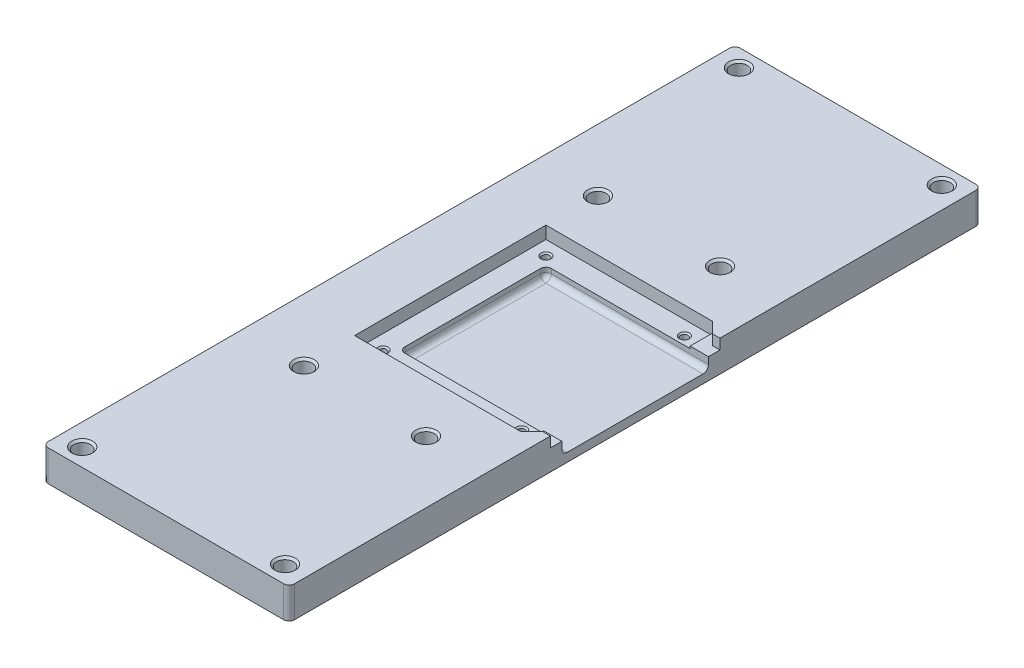
SolidWorks part; units mm, degrees
ref_plane "Front Plane" through (0, 0, 0) normal (0, 0, 1) x (1, 0, 0)
ref_plane "Top Plane" through (0, 0, 0) normal (0, 1, 0) x (1, 0, 0)
ref_plane "Right Plane" through (0, 0, 0) normal (1, 0, 0) x (0, 0, -1)
sketch "Sketch1" plane through (0, 0, 0) normal (0, 1, 0) x (1, 0, 0)
  line L0 (0, -112.5) -> (0, 112.5) construction
  line L1 (45.375, 112.5) -> (-45.375, 112.5) construction
  line L2 (-45.375, 112.5) -> (-45.375, -112.5)
  line L3 (-45.375, 0) -> (45.375, 0) construction
  line L4 (-45.375, 112.5) -> (-45.375, 125.5)
  line L5 (-43.375, 127.5) -> (43.375, 127.5)
  line L6 (0, 127.5) -> (0, 112.5) construction
  line L7 (45.375, 112.5) -> (45.375, 125.5)
  line L8 (45.375, 112.5) -> (45.375, -112.5)
  line L9 (0, -127.5) -> (0, -112.5) construction
  line L10 (45.375, -112.5) -> (-45.375, -112.5) construction
  line L11 (45.375, -112.5) -> (45.375, -125.5)
  line L12 (-43.375, -127.5) -> (43.375, -127.5)
  line L13 (-45.375, -112.5) -> (-45.375, -125.5)
  line L14 (-45.375, 115.5) -> (45.375, 115.5) construction
  circle A1 centre (-37.375, 121) radius 3.075 construction
  circle A2 centre (37.375, 121) radius 3.075 construction
  circle A5 centre (37.375, -121) radius 3.075 construction
  circle A6 centre (-37.375, -121) radius 3.075 construction
  arc A8 (-43.375, -127.5) -> (-45.375, -125.5) centre (-43.375, -125.5) cw
  arc A9 (45.375, -125.5) -> (43.375, -127.5) centre (43.375, -125.5) cw
  arc A10 (45.375, 125.5) -> (43.375, 127.5) centre (43.375, 125.5) ccw
  arc A11 (-45.375, 125.5) -> (-43.375, 127.5) centre (-43.375, 125.5) cw
  circle A12 centre (-22.5, 54.175) radius 3.075 construction
  circle A13 centre (22.5, 54.175) radius 3.075 construction
  circle A14 centre (22.5, -54.175) radius 3.075 construction
  circle A15 centre (-22.5, -54.175) radius 3.075 construction
  point P24 (0, 0)
  point P36 (-45.375, -127.5)
  point P39 (45.375, -127.5)
  point P42 (45.375, 127.5)
  point P45 (-45.375, 127.5)
  dimension "D5" = 22.5
  dimension "D10" = 2
  dimension "D3" = 6.15
  dimension "D1" = 45.375
  dimension "D2" = 112.5
  dimension "D4" = 6.5
  dimension "D6" = 8
  dimension "D7" = 8.5
  dimension "D8" = 12
  dimension "D9" = 3
  dimension "D11" = 127.5
  dimension "D12" = 54.175
extrude "Boss-Extrude1" add sketch "Sketch1" along normal blind 11.5
sketch "Sketch3" plane through (0, 11.5, 0) normal (0, 1, 0) x (1, 0, 0)
  line L0 (0, 0) -> (-45.375, 0) construction
  line L1 (-45.375, 125.5) -> (-45.375, -125.5) construction
  line L2 (0, 0) -> (0, 127.5) construction
  line L3 (43.375, 127.5) -> (-43.375, 127.5) construction
  line L4 (3.96, -16.3) -> (3.96, 16.3)
  line L5 (-2.46, -17.8) -> (2.46, -17.8)
  line L6 (-3.96, 16.3) -> (-3.96, -16.3)
  line L7 (2.46, 17.8) -> (-2.46, 17.8)
  line L8 (0, 17.8) -> (0, -17.8) construction
  line L9 (13.25, 0) -> (0, 0) construction
  line L10 (16.15, 10.025) -> (10.35, 10.025)
  line L11 (16.15, 10.025) -> (16.15, -10.025)
  line L12 (16.15, -10.025) -> (10.35, -10.025)
  line L13 (10.35, 10.025) -> (10.35, -10.025)
  line L14 (16.15, 10.025) -> (10.35, -10.025) construction
  line L15 (16.15, -10.025) -> (10.35, 10.025) construction
  line L16 (13.25, 0) -> (13.25, 10.025) construction
  line L17 (-16.15, 10.025) -> (-16.15, -10.025)
  line L18 (-16.15, -10.025) -> (-10.35, -10.025)
  line L23 (-16.15, 10.025) -> (-10.35, 10.025)
  line L24 (-10.35, 10.025) -> (-10.35, -10.025)
  arc A0 (-2.46, 17.8) -> (-3.96, 16.3) centre (-2.46, 16.3) ccw
  arc A1 (3.96, 16.3) -> (2.46, 17.8) centre (2.46, 16.3) ccw
  arc A2 (2.46, -17.8) -> (3.96, -16.3) centre (2.46, -16.3) ccw
  arc A3 (-3.96, -16.3) -> (-2.46, -17.8) centre (-2.46, -16.3) ccw
  point P9 (0, 0)
  point P23 (0, 0)
  dimension "D2" = 1.5
  dimension "D1" = 35.6
  dimension "D3" = 7.92
  dimension "D4" = 20.05
  dimension "D5" = 5.8
  dimension "D6" = 13.25
sketch "Sketch4" plane through (0, 11.5, 0) normal (0, 1, 0) x (1, 0, 0)
  circle A0 centre (-37.375, -121) radius 3.075 construction
  circle A1 centre (37.375, -121) radius 3.075 construction
  circle A2 centre (37.375, 121) radius 3.075 construction
  circle A3 centre (-22.5, -54.175) radius 3.075 construction
  circle A4 centre (22.5, -54.175) radius 3.075 construction
  circle A5 centre (-37.375, 121) radius 3.075 construction
  circle A6 centre (22.5, 54.175) radius 3.075 construction
  circle A7 centre (-22.5, 54.175) radius 3.075 construction
  circle A8 centre (-37.375, -121) radius 3.075
  circle A9 centre (37.375, -121) radius 3.075
  circle A10 centre (37.375, 121) radius 3.075
  circle A13 centre (-37.375, 121) radius 3.075
  circle A14 centre (-22.5, -54.175) radius 3.075
  circle A15 centre (22.5, -54.175) radius 3.075
  circle A16 centre (22.5, 54.175) radius 3.075
  circle A17 centre (-22.5, 54.175) radius 3.075
extrude "Cut-Extrude1" cut sketch "Sketch4" against normal blind 6
sketch "Sketch21" plane through (0, 11.5, 0) normal (0, 1, 0) x (1, 0, 0)
  line L0 (38.5, 35) -> (-22.5, 35) construction
  line L1 (38.5, 35) -> (42.5, 31) construction
  line L2 (-22.5, 35) -> (-22.5, -35) construction
  line L3 (-22.5, 0) -> (0, 0) construction
  line L4 (0, 0) -> (38.5, 0) construction
  line L5 (38.5, -35) -> (38.5, 35) construction
  line L6 (38.5, -35) -> (-22.5, -35) construction
  line L7 (42.5, 31) -> (45.375, 31) construction
  line L8 (45.375, -125.5) -> (45.375, 125.5) construction
  line L9 (45.375, 31) -> (45.375, -31)
  line L10 (45.375, 0) -> (38.5, 0) construction
  line L11 (42.5, -31) -> (45.375, -31) construction
  line L12 (38.5, -35) -> (42.5, -31) construction
  line L13 (42.6036, 31.25) -> (45.375, 31.25)
  line L14 (38.6036, 35.25) -> (42.6036, 31.25)
  line L15 (38.6036, 35.25) -> (-22.75, 35.25)
  line L16 (-22.75, 35.25) -> (-22.75, -35.25)
  line L17 (38.6036, -35.25) -> (-22.75, -35.25)
  line L18 (38.6036, -35.25) -> (42.6036, -31.25)
  line L19 (42.6036, -31.25) -> (45.375, -31.25)
  line L20 (45.375, -31.25) -> (45.375, -31)
  line L21 (45.375, 31) -> (45.375, 31.25)
  circle A0 centre (-17.5, 30) radius 1.6 construction
  circle A1 centre (33.5, 30) radius 1.6 construction
  circle A2 centre (33.5, -30) radius 1.6 construction
  circle A3 centre (-17.5, -30) radius 1.6 construction
  dimension "D8" = 3.2
  dimension "D1" = 22.5
  dimension "D2" = 61
  dimension "D3" = 35
  dimension "D4" = 5
  dimension "D5" = 5
  dimension "D6" = 5
  dimension "D7" = 5
  dimension "D9" = 45
  dimension "D10" = 4
  dimension "D12" = 2.875
  dimension "D11" = 0.25
extrude "Cut-Extrude6" cut sketch "Sketch21" against normal blind 4.6
sketch "Sketch24" plane through (0, 6.9, 0) normal (0, 1, 0) x (1, 0, 0)
  line L0 (45.375, 27) -> (-14.5, 27)
  line L2 (-14.5, 27) -> (-14.5, -27)
  line L3 (-14.5, -27) -> (45.375, -27)
  line L4 (45.375, -27) -> (45.375, 27)
  line L8 (38.5, 35) -> (-22.5, 35) construction
  line L10 (-22.5, 35) -> (-22.5, -35) construction
  line L11 (38.5, -35) -> (-22.5, -35) construction
  line L12 (45.375, -31.25) -> (45.375, 31.25) construction
  dimension "D1" = 8
  dimension "D2" = 8
  dimension "D3" = 8
extrude "Cut-Extrude3" cut sketch "Sketch24" against normal blind 3.7 and the other way through all
sketch "Sketch25" plane through (0, 6.9, 0) normal (0, 1, 0) x (1, 0, 0)
  circle A0 centre (33.5, 30) radius 1.35
  circle A1 centre (-17.5, 30) radius 1.35
  circle A2 centre (33.5, -30) radius 1.35
  circle A3 centre (-17.5, -30) radius 1.35
  dimension "D1" = 2.7
extrude "Cut-Extrude4" cut sketch "Sketch25" against normal blind 5
chamfer "Chamfer4" distance 0.5 angle 45 4 edges at (-17.5, 6.9, 31.35) (33.5, 6.9, 31.35) (33.5, 6.9, -28.65) (-17.5, 6.9, -28.65)
fillet "Fillet1" radius 2 5 edges at (15.4375, 3.2, 27) (-14.5, 5.05, 27) (-14.5, 5.05, -27) (-14.5, 3.2, 0) (15.4375, 3.2, -27)
sketch "Sketch26" plane through (0, 6.9, 0) normal (0, 1, 0) x (1, 0, 0)
  line L0 (0, 0) -> (45.375, 0) construction
  line L1 (45.375, -25) -> (45.375, 25) construction
  line L2 (38.6036, 35.25) -> (38.6036, 27)
  line L3 (45.375, 27) -> (-12.5, 27) construction
  line L4 (38.6036, 27) -> (45.375, 27)
  line L5 (45.375, 27) -> (45.375, 31.25)
  line L6 (45.375, 31.25) -> (42.6036, 31.25)
  line L7 (42.6036, 31.25) -> (38.6036, 35.25)
  line L8 (42.6036, -31.25) -> (38.6036, -35.25)
  line L9 (45.375, -31.25) -> (42.6036, -31.25)
  line L10 (45.375, -27) -> (45.375, -31.25)
  line L11 (38.6036, -27) -> (45.375, -27)
  line L12 (38.6036, -35.25) -> (38.6036, -27)
extrude "Boss-Extrude2" add sketch "Sketch26" along normal blind 0.8
chamfer "Chamfer5" distance 0.75 angle 45 8 edges at (-37.375, 11.5, 124.075) (37.375, 11.5, 124.075) (-22.5, 11.5, 57.25) (22.5, 11.5, 57.25) (22.5, 11.5, -51.1) (-22.5, 11.5, -51.1) (-37.375, 11.5, -117.925) (37.375, 11.5, -117.925)
equation "\"D5@Sketch21\"=\"D4@Sketch21\""
equation "\"D6@Sketch21\"=\"D4@Sketch21\""
equation "\"D7@Sketch21\"=\"D4@Sketch21\""
equation "\"D2@Sketch24\"=\"D1@Sketch24\""
equation "\"D3@Sketch24\"=\"D1@Sketch24\""
